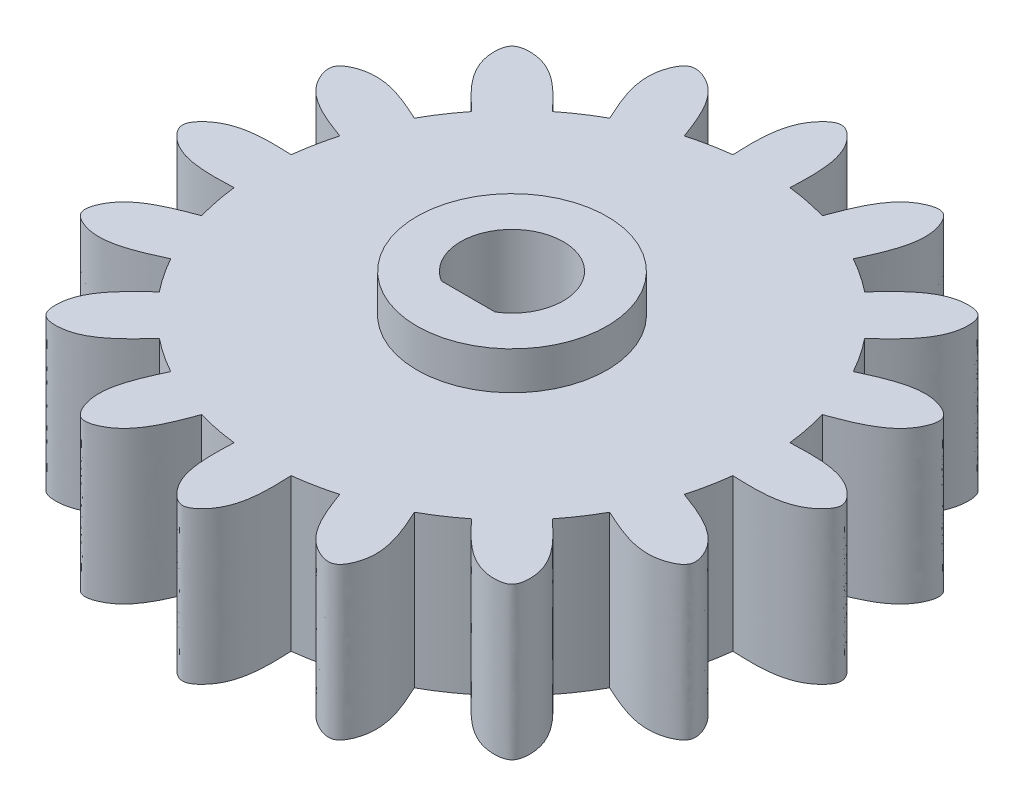
SolidWorks part; units mm, degrees
ref_plane "Front Plane" through (0, 0, 0) normal (0, 0, 1) x (1, 0, 0)
ref_plane "Top Plane" through (0, 0, 0) normal (0, 1, 0) x (1, 0, 0)
ref_plane "Right Plane" through (0, 0, 0) normal (1, 0, 0) x (0, 0, -1)
sketch "Sketch1" plane through (0, 0, 0) normal (0, 1, 0) x (1, 0, 0)
  line L0 (0, 0) -> (0, 10) construction
  circle A12 centre (0, 0) radius 13.2
  point P43 (0, 0)
  dimension "D1" = 26.4
extrude "Boss-Extrude1" add sketch "Sketch1" along normal blind 10
sketch "Sketch4" plane through (0, 0, 0) normal (0, -1, 0) x (1, 0, 0)
  line L0 (-1.5, -13.1145) -> (1.5, -13.1145)
  circle A1 centre (0, 0) radius 13.2 construction
  spline S0 degree 3 poles (1.5, -13.1145) (1.5223, -13.6797) (1.5744, -14.9965) (1.1993, -16.61) (0, -17.5178) (-1.1993, -16.61) (-1.5744, -14.9965) (-1.5223, -13.6797) (-1.5, -13.1145) knots 0 0 0 0 0.178316 0.415433 0.5 0.584567 0.821684 1 1 1 1
  dimension "D1" = 3
  dimension "D2" = 3
  dimension "D3" = 4.2143
  dimension "D4" = 1.4
  dimension "D5" = 0.4
  dimension "D6" = 0.7
  dimension "D7" = 1.7
sketch "Sketch2" plane through (0, 10, 0) normal (0, 1, 0) x (1, 0, 0)
  circle A0 centre (0, 0) radius 5
  dimension "D1" = 10
extrude "Boss-Extrude2" add sketch "Sketch2" along normal blind 2
extrude "Boss-Extrude5" add sketch "Sketch4" against normal blind 10
pattern_circular "CirPattern1" count 16 over 360 of "Boss-Extrude5"
sketch "Sketch5" plane through (0, 12, 0) normal (0, 1, 0) x (1, 0, 0)
  line L0 (1.4142, -2.3) -> (-1.4142, -2.3)
  arc A0 (1.4142, -2.3) -> (-1.4142, -2.3) centre (0, 0) ccw
  point P5 (0, -2.3)
  dimension "D1" = 5.4
  dimension "D2" = 2.3
extrude "Cut-Extrude1" cut sketch "Sketch5" against normal through all contours A0 L0
sketch "Sketch6" plane through (0, 0, 0) normal (0, -1, 0) x (1, 0, 0)
  circle A2 centre (0, 0) radius 36.4787
extrude "Cut-Extrude2" cut sketch "Sketch6" against normal blind 2 contours A2
